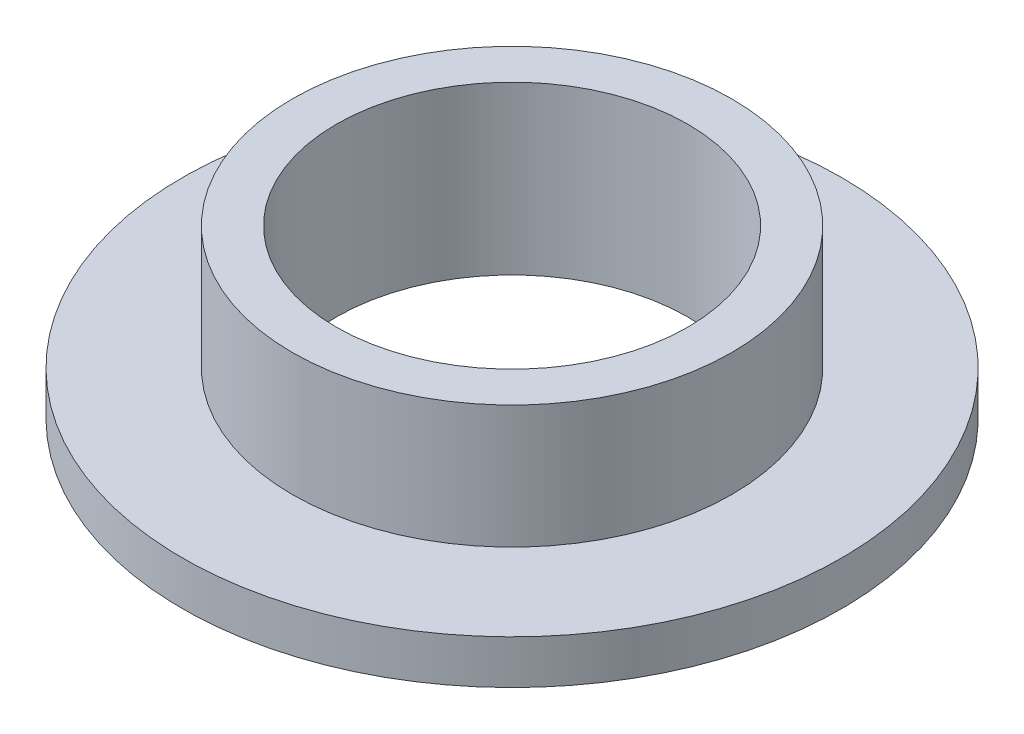
SolidWorks part; units mm, degrees
material "acero"
ref_plane "Alzado" through (0, 0, 0) normal (0, 0, 1) x (1, 0, 0)
ref_plane "Planta" through (0, 0, 0) normal (0, 1, 0) x (1, 0, 0)
ref_plane "Vista lateral" through (0, 0, 0) normal (1, 0, 0) x (0, 0, -1)
sketch "Croquis1" plane through (0, 0, 0) normal (0, 0, 1) x (1, 0, 0)
  line L0 (0, 0) -> (0, 57.7811) construction
  line L1 (-4, 3.8) -> (-4, 0)
  line L2 (-4, 0) -> (-7.5, 0)
  line L3 (-7.5, 0) -> (-7.5, 1)
  line L4 (-7.5, 1) -> (-5, 1)
  line L5 (-5, 1) -> (-5, 3.8)
  line L6 (-5, 3.8) -> (-4, 3.8)
  dimension "D1" = 8
  dimension "D2" = 10
  dimension "D3" = 1
  dimension "D4" = 15
  dimension "D5" = 3.8
revolve "Revolución1" add sketch "Croquis1" angle 360 about L0
